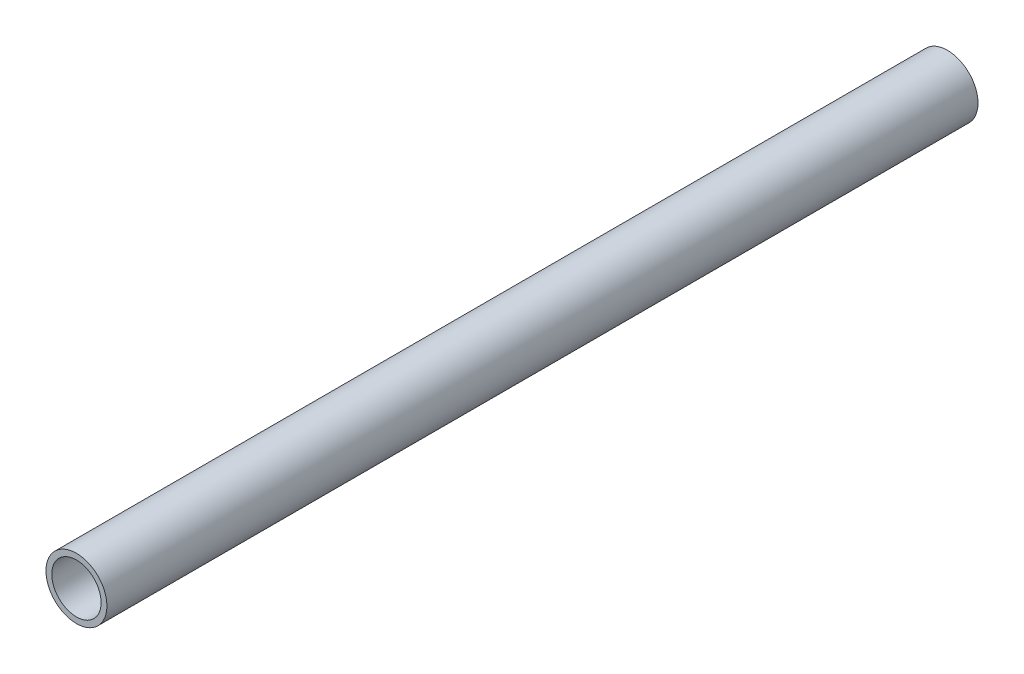
SolidWorks part; units mm, degrees
material "AISI 4130 Steel, annealed at 865C"
ref_plane "Front Plane" through (0, 0, 0) normal (0, 0, 1) x (1, 0, 0)
ref_plane "Top Plane" through (0, 0, 0) normal (0, 1, 0) x (1, 0, 0)
ref_plane "Right Plane" through (0, 0, 0) normal (1, 0, 0) x (0, 0, -1)
sketch "Sketch1" plane through (0, 0, 0) normal (0, 0, 1) x (1, 0, 0)
  circle A0 centre (0, 0) radius 6.477
  circle A1 centre (0, 0) radius 8.001
  dimension "D1" = 12.954
  dimension "D2" = 16.002
extrude "Boss-Extrude1" add sketch "Sketch1" along normal blind 228.6
sketch "Sketch2" plane through (0, 0, 0) normal (1, 0, 0) x (0, 0, -1)
  line L0 (0, 3.175) -> (-31.75, 3.175)
  line L1 (0, 8.8011) -> (0, -8.8011) construction
  line L2 (-31.75, -3.175) -> (0, -3.175)
  line L3 (-33.274, 1.651) -> (-33.274, -1.651)
  line L4 (0, -8.001) -> (0, 8.001) construction
  arc A0 (-33.274, 1.651) -> (-31.75, 3.175) centre (-31.75, 1.651) cw
  arc A1 (-31.75, -3.175) -> (-33.274, -1.651) centre (-31.75, -1.651) cw
  dimension "D5" = 31.75
  dimension "D6" = 33.274
  dimension "D1" = 33.274
  dimension "D2" = 31.75
  dimension "D3" = 6.35
  dimension "D4" = 3.175
